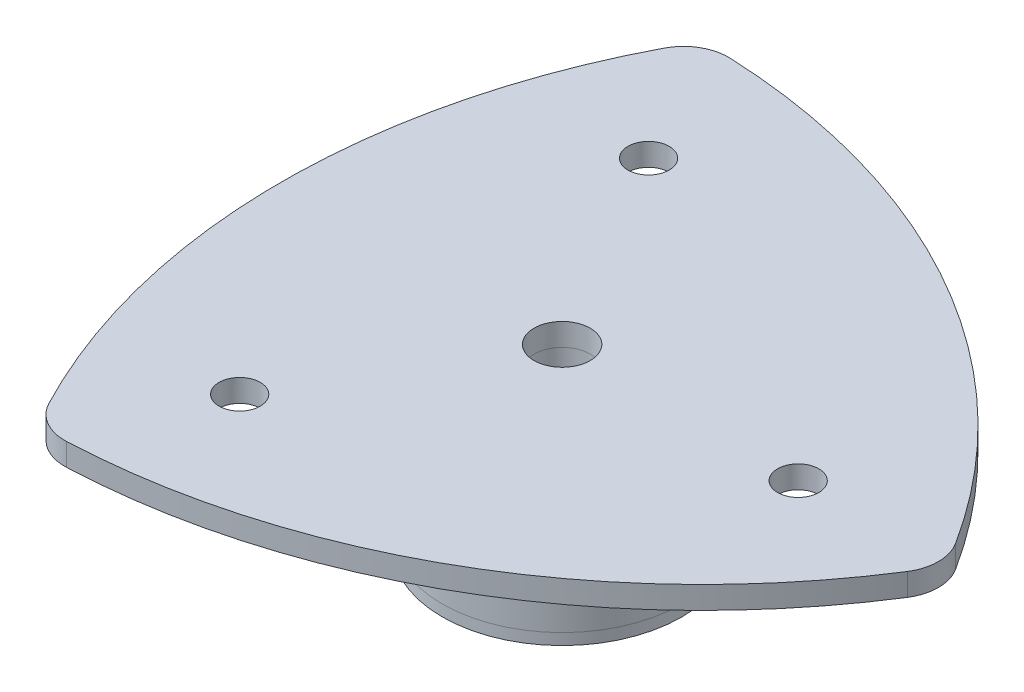
SolidWorks part; units mm, degrees
other "橡胶层"
other "内层"
other "法兰" parameters "D1"=91.2712, "D2"=52.3565, "D3"=15.2611, "D4"=30.161, "D5"=25.3326, "D6"=22.5, "D7"=2
ref_plane "前视基准面" through (0, 0, 0) normal (0, 0, 1) x (1, 0, 0)
ref_plane "上视基准面" through (0, 0, 0) normal (0, 1, 0) x (1, 0, 0)
ref_plane "右视基准面" through (0, 0, 0) normal (1, 0, 0) x (0, 0, -1)
other "Configuration Table"
sketch "草图2" plane through (0, 0, 0) normal (0, 0, 1) x (1, 0, 0)
  line L0 (0, 0) -> (0, 101.7223) construction
  line L1 (30, 0) -> (32, 0)
  line L2 (32, 0) -> (32, 3)
  line L3 (32, 3) -> (9.5, 3)
  line L4 (9.5, 3) -> (9.5, 41)
  line L5 (9.5, 41) -> (7.5, 41)
  line L6 (7.5, 41) -> (7.5, 1)
  line L7 (7.5, 1) -> (30, 1)
  line L8 (30, 1) -> (30, 0)
  dimension "D1" = 32
  dimension "D2" = 30
  dimension "D3" = 1
  dimension "D4" = 7.5
  dimension "D5" = 2
  dimension "D6" = 2
  dimension "D7" = 41
revolve "旋转1" add sketch "草图2" angle 360 about L0
sketch "草图3" plane through (0, 0, 0) normal (0, 0, 1) x (1, 0, 0)
  line L0 (0, 0) -> (0, 63.3088) construction
  line L1 (32, 3) -> (-32, 3) construction
  line L2 (9.5, 3) -> (9.5, 41) construction
  line L3 (32, 3) -> (-32, 3)
  line L4 (9.5, 3) -> (9.5, 41)
  line L5 (32, 0) -> (32, 3) construction
  line L6 (9.5, 3) -> (32, 3)
  line L7 (9.5, 3) -> (9.5, 41)
  line L8 (9.5, 41) -> (32, 41)
  line L9 (32, 3) -> (32, 41)
  line L10 (9.5, 41) -> (-9.5, 41) construction
revolve "旋转2" add sketch "草图3" angle 360 about L0
sketch "草图4" plane through (0, 0, 0) normal (0, 0, 1) x (1, 0, 0)
  line L0 (0, 0) -> (0, 49.9526) construction
  line L1 (32, 3) -> (32, 41) construction
  line L2 (32, 41) -> (-32, 41) construction
  line L3 (32, 3) -> (32, 41)
  line L4 (32, 41) -> (-32, 41)
  line L5 (32, 27) -> (38, 27)
  line L6 (38, 27) -> (38, 41)
  line L7 (38, 41) -> (75, 41)
  line L8 (75, 41) -> (75, 47)
  line L9 (75, 47) -> (32, 47)
  line L10 (32, 47) -> (7.5, 47)
  line L11 (7.5, 47) -> (7.5, 41)
  line L12 (7.5, 41) -> (32, 41)
  dimension "D1" = 75
  dimension "D2" = 6
  dimension "D3" = 20
  dimension "D4" = 6
  dimension "D5" = 7.5
revolve "旋转3" add sketch "草图4" angle 360 about L0
sketch "草图5" plane through (0, 47, 0) normal (0, 1, 0) x (1, 0, 0)
  circle A0 centre (63, 0) radius 5.5
  circle A1 centre (0, 0) radius 75 construction
  circle A2 centre (0, 0) radius 75
  circle A3 centre (102.4519, 0) radius 177.4519
  circle A4 centre (-51.226, -88.726) radius 177.4519
  circle A5 centre (-31.5, -54.5596) radius 5.5
  circle A6 centre (-51.226, 88.726) radius 177.4519
  circle A7 centre (-31.5, 54.5596) radius 5.5
  circle M8 centre (0, 0) radius 75
  dimension "D1" = 11
  dimension "D2" = 63
  dimension "D3" = 3
extrude "凸台-拉伸1" add sketch "草图5" against normal up to surface (6 mm away) contours A2 A4 A3 | A3 A6 M8 | A2 A6 A4
sketch "草图6" plane through (0, 47, 0) normal (0, 1, 0) x (1, 0, 0)
  circle A0 centre (-31.5, 54.5596) radius 5.5 construction
  circle A1 centre (-31.5, -54.5596) radius 5.5 construction
  circle A2 centre (63, 0) radius 5.5 construction
  circle A3 centre (-31.5, 54.5596) radius 5.5
  circle A4 centre (-31.5, -54.5596) radius 5.5
  circle A5 centre (63, 0) radius 5.5
extrude "切除-拉伸1" cut sketch "草图6" against normal up to surface (6 mm away)
fillet "圆角1" radius 12 3 edges at (-51.226, 44, -88.726) (102.4519, 44, 0) (-51.226, 44, 88.726)
equation "\"活塞杆直径\"= 15"
equation "\"间隙\"= 0.5"
equation "\"顶胶中心孔\"= \"活塞杆直径\" + 2 * \"间隙\""
equation "\"顶胶外径\"= 150"
equation "\"顶胶高\"= 41"
equation "\"下端面止口内径\"= 60"
equation "\"下端面止口深\"= 1"
equation "\"下端面止口外径\"= 64"
equation "\"D1@草图2\"=\"下端面止口外径\"/2"
equation "\"D2@草图2\"=\"下端面止口内径\"/2"
equation "\"D3@草图2\"=\"下端面止口深\""
equation "\"D4@草图2\"=\"活塞杆直径\"/2"
equation "\"内层壁厚\"= 2"
equation "\"外层壁厚\"= 6"
equation "\"法兰高\"= 20"
equation "\"连接螺栓孔\"=11"
equation "\"螺栓距边缘\"= 12"
equation "\"D5@草图2\"=\"内层壁厚\""
equation "\"D6@草图2\"=\"内层壁厚\""
equation "\"D7@草图2\"=\"顶胶高\""
equation "\"D1@草图4\"=\"顶胶外径\"/2"
equation "\"D2@草图4\"=\"外层壁厚\""
equation "\"D3@草图4\"=\"法兰高\""
equation "\"D4@草图4\"=\"外层壁厚\""
equation "\"D5@草图4\"=\"活塞杆直径\"/2"
equation "\"D1@草图5\"=\"连接螺栓孔\""
equation "\"D2@草图5\"=\"顶胶外径\"/2 -\"螺栓距边缘\""
